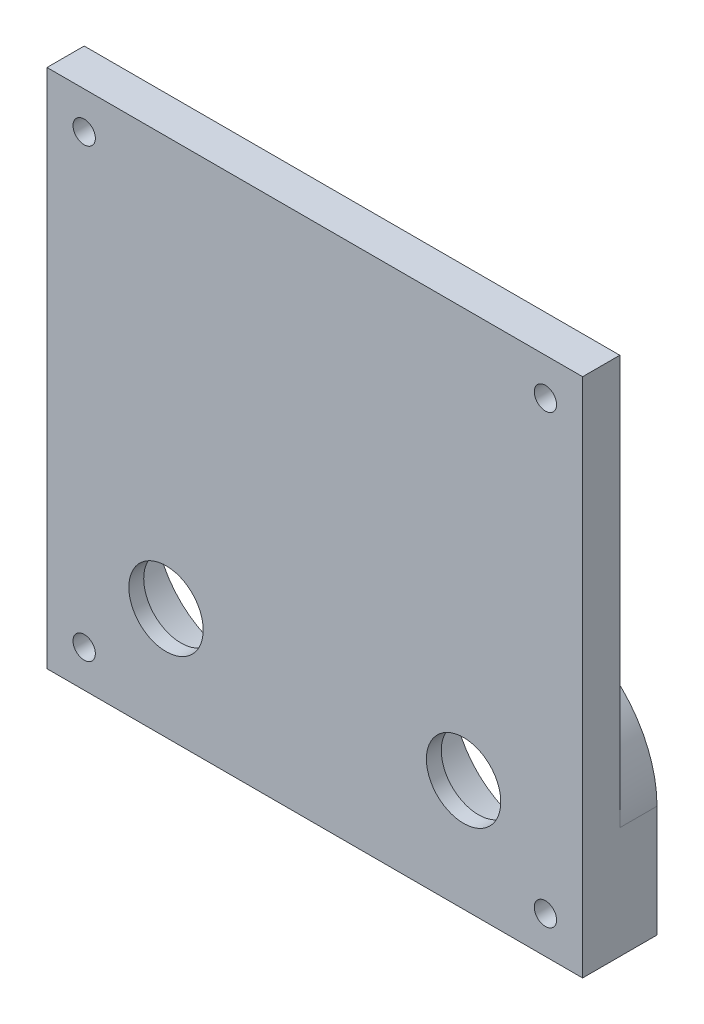
SolidWorks part; units mm, degrees
ref_plane "Front Plane" through (0, 0, 0) normal (0, 0, 1) x (1, 0, 0)
ref_plane "Top Plane" through (0, 0, 0) normal (0, 1, 0) x (1, 0, 0)
ref_plane "Right Plane" through (0, 0, 0) normal (1, 0, 0) x (0, 0, -1)
sketch "Sketch1" plane through (0, 0, 0) normal (0, 0, 1) x (1, 0, 0)
  line L1 (0, 0) -> (70, 0)
  line L2 (0, 0) -> (0, 70)
  line L3 (0, 70) -> (70, 70)
  line L4 (70, 0) -> (70, 70)
  dimension "D1" = 70
  dimension "D2" = 70
extrude "Boss-Extrude1" add sketch "Sketch1" along normal blind 10
sketch "Sketch2" plane through (0, 0, 10) normal (0, 0, 1) x (1, 0, 0)
  line L0 (70, 70) -> (0, 70) construction
  circle A0 centre (35, 49) radius 12
  circle A1 centre (19.5, 65) radius 2
  circle A2 centre (50.5, 65) radius 2
  circle A3 centre (19.5, 34) radius 2
  circle A4 centre (50.5, 34) radius 2
  circle A5 centre (15, 15) radius 11.5
  circle A6 centre (55, 15) radius 11.5
  point P17 (35, 70)
  dimension "D1" = 24
  dimension "D2" = 4
  dimension "D3" = 4
  dimension "D4" = 4
  dimension "D5" = 4
  dimension "D15" = 23
  dimension "D16" = 23
  dimension "D6" = 21
  dimension "D7" = 5
  dimension "D8" = 5
  dimension "D9" = 31
  dimension "D10" = 31
  dimension "D11" = 31
  dimension "D12" = 31
  dimension "D13" = 15.5
  dimension "D14" = 0
  dimension "D17" = 40
  dimension "D18" = 15
  dimension "D19" = 15
  dimension "D20" = 15
extrude "Cut-Extrude1" cut sketch "Sketch2" against normal blind 10
sketch "Sketch3" plane through (0, 0, 0) normal (-1, 0, 0) x (0, 0, 1)
  line L1 (0, 70) -> (10, 70)
  line L2 (0, 70) -> (0, 0)
  line L3 (0, 0) -> (10, 0)
  line L4 (10, 70) -> (10, 0)
extrude "Boss-Extrude2" add sketch "Sketch3" along normal blind 15
sketch "Sketch4" plane through (70, 0, 0) normal (1, 0, 0) x (0, 0, -1)
  line L1 (0, 70) -> (-10, 70)
  line L2 (0, 70) -> (0, 0)
  line L3 (0, 0) -> (-10, 0)
  line L4 (-10, 70) -> (-10, 0)
extrude "Boss-Extrude3" add sketch "Sketch4" along normal blind 15 contours L4 L3 L2 L1
sketch "Sketch5" plane through (0, 0, 10) normal (0, 0, 1) x (1, 0, 0)
  circle A0 centre (15, 15) radius 11.5
  circle A1 centre (55, 15) radius 11.5
  circle A2 centre (15, 15) radius 4
  circle A3 centre (55, 15) radius 4
  dimension "D1" = 8
  dimension "D2" = 8
extrude "Boss-Extrude4" add sketch "Sketch5" against normal blind 2
sketch "Sketch6" plane through (0, 0, 0) normal (0, 0, -1) x (-1, 0, 0)
  line L0 (-85, 70) -> (-85, 0) construction
  line L1 (-85, 70) -> (15, 70) construction
  circle A0 centre (-80, 65) radius 1.5
  circle A1 centre (-80, 5) radius 1.5
  circle A2 centre (10, 65) radius 1.6487
  circle A3 centre (10, 5) radius 1.5
  dimension "D4" = 3
  dimension "D5" = 3
  dimension "D8" = 3
  dimension "D1" = 5
  dimension "D2" = 5
  dimension "D3" = 5
  dimension "D6" = 5
  dimension "D7" = 5
extrude "Cut-Extrude3" cut sketch "Sketch6" against normal blind 10
sketch "Sketch7" plane through (0, 0, 0) normal (0, 0, -1) x (-1, 0, 0)
  circle A0 centre (-35, 49) radius 11.9867
  circle A1 centre (-50.5, 65) radius 2
  circle A2 centre (-19.5, 65) radius 2
  circle A3 centre (-19.5, 34) radius 2
  circle A4 centre (-50.5, 34) radius 2
extrude "Boss-Extrude5" add sketch "Sketch7" against normal blind 10
sketch "Sketch8" plane through (0, 0, 0) normal (0, 0, -1) x (-1, 0, 0)
  line L0 (-85, 70) -> (15, 70) construction
  circle A0 centre (-33.9287, 49) radius 12
  circle A3 centre (-55, 15) radius 4 construction
  dimension "D1" = 24
  dimension "D2" = 21
  dimension "D3" = 40
extrude "Cut-Extrude4" cut sketch "Sketch8" against normal blind 10
sketch "Sketch9" plane through (0, 0, 0) normal (0, 0, -1) x (-1, 0, 0)
  circle A0 centre (-49.4287, 64.5) radius 2
  arc A1 (-34.4643, 37.012) -> (-34.4643, 60.988) centre (-33.9287, 49) ccw construction
  circle A2 centre (-49.4287, 33.5) radius 2
  circle A3 centre (-18.4287, 33.5) radius 2
  circle A4 centre (-18.4287, 64.5) radius 2
  point P5 (-21.9287, 49)
  dimension "D3" = 4
  dimension "D5" = 4
  dimension "D6" = 4
  dimension "D8" = 4
  dimension "D1" = 15.5
  dimension "D2" = 15.5
  dimension "D4" = 31
  dimension "D7" = 31
extrude "Cut-Extrude5" cut sketch "Sketch9" against normal blind 10
sketch "Sketch14" plane through (0, 0, 0) normal (0, 0, -1) x (-1, 0, 0)
  line L0 (-85, 0) -> (-85, 70)
  line L1 (-85, 70) -> (15, 70)
  line L2 (15, 70) -> (15, 0)
  line L3 (15, 70) -> (15, 0) construction
  line L4 (15, 0) -> (-85, 0) construction
  line L5 (-71, 15) -> (-71, 0)
  line L6 (-71, 0) -> (-85, 0)
  line L7 (-39, 15) -> (-39, 0)
  line L8 (-39, 0) -> (-31, 0)
  line L9 (-31, 0) -> (-31, 15)
  line L10 (1, 15) -> (1, 0)
  line L11 (1, 0) -> (15, 0)
  arc A0 (-31, 15) -> (1, 15) centre (-15, 15) cw
  arc A1 (-39, 15) -> (-71, 15) centre (-55, 15) ccw
  dimension "D1" = 16
  dimension "D2" = 16
extrude "Cut-Extrude7" cut sketch "Sketch14" against normal blind 5 contours L2 L11 L10 A0 L9 L8 L7 A1 L5 L6 L0 L1
sketch "Sketch15" plane through (0, 0, 5) normal (0, 0, -1) x (-1, 0, 0)
  line L1 (-71, 0) -> (-85, 0)
  line L2 (-71, 0) -> (-71, 70)
  line L3 (-71, 70) -> (-85, 70)
  line L4 (-85, 0) -> (-85, 70)
  line L5 (1, 0) -> (15, 0)
  line L6 (1, 0) -> (1, 70)
  line L7 (1, 70) -> (15, 70)
  line L8 (15, 0) -> (15, 70)
extrude "Cut-Extrude8" cut sketch "Sketch15" against normal blind 5
sketch "Sketch16" plane through (0, 0, 5) normal (0, 0, -1) x (-1, 0, 0)
  line L0 (-71, 70) -> (1, 70) construction
  line L1 (-71, 15) -> (-71, 70) construction
  line L2 (-39, 0) -> (-71, 0) construction
  line L4 (1, 15) -> (1, 0) construction
  circle A0 centre (-66, 65) radius 1.5
  circle A1 centre (-66, 5) radius 1.5
  circle A2 centre (-4, 5) radius 1.5
  circle A3 centre (-4, 65) radius 1.5
  dimension "D1" = 3
  dimension "D5" = 3
  dimension "D6" = 3
  dimension "D8" = 3
  dimension "D2" = 5
  dimension "D3" = 5
  dimension "D4" = 5
  dimension "D7" = 5
extrude "Cut-Extrude9" cut sketch "Sketch16" along normal blind 19 and the other way blind 48
sketch "Sketch17" plane through (0, 0, 8) normal (0, 0, -1) x (-1, 0, 0)
  circle A0 centre (-15, 15) radius 5
  circle A1 centre (-55, 15) radius 5
  dimension "D1" = 10
  dimension "D2" = 10
extrude "Cut-Extrude10" cut sketch "Sketch17" against normal blind 19
sketch "Sketch18" plane through (0, 0, 5) normal (0, 0, -1) x (-1, 0, 0)
  line L0 (-71, 70) -> (1, 70) construction
  line L1 (-59.5583, 70) -> (-15, 70)
  line L2 (-59.5583, 70) -> (-59.5583, 31)
  line L3 (-59.5583, 31) -> (-15, 31)
  line L4 (-15, 70) -> (-15, 31)
  arc A0 (1, 15) -> (-31, 15) centre (-15, 15) ccw construction
extrude "Boss-Extrude6" add sketch "Sketch18" against normal blind 5
